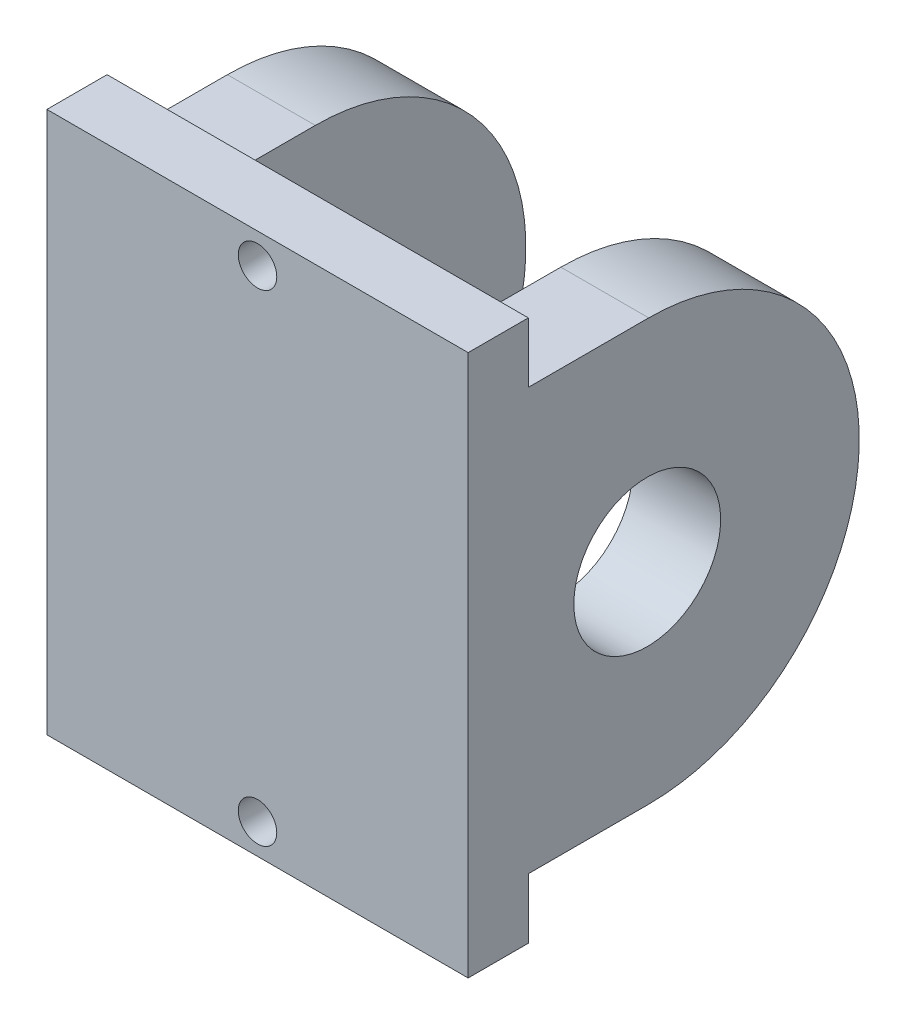
SolidWorks part; units mm, degrees
ref_plane "前视基准面" through (0, 0, 0) normal (0, 0, 1) x (1, 0, 0)
ref_plane "上视基准面" through (0, 0, 0) normal (0, 1, 0) x (1, 0, 0)
ref_plane "右视基准面" through (0, 0, 0) normal (1, 0, 0) x (0, 0, -1)
other "Configuration Table"
sketch "草图1" plane through (0, 0, 0) normal (0, 0, 1) x (1, 0, 0)
  line L1 (-17.5, 17.5) -> (17.5, 17.5)
  line L2 (-17.5, 17.5) -> (-17.5, -17.5)
  line L3 (-17.5, -17.5) -> (17.5, -17.5)
  line L4 (17.5, 17.5) -> (17.5, -17.5)
  line L5 (0, -17.5) -> (0, 17.5) construction
  line L6 (-17.5, 0) -> (17.5, 0) construction
  point P0 (0, 0)
  dimension "D1" = 35
  dimension "D2" = 35
extrude "凸台-拉伸1" add sketch "草图1" along normal blind 5
sketch "草图2" plane through (-17.5, 0, 0) normal (-1, 0, 0) x (0, 0, 1)
  line L1 (5, 17.5) -> (-10, 17.5)
  line L2 (5, 17.5) -> (5, -17.5)
  line L3 (5, -17.5) -> (-10, -17.5)
  line L5 (5, -17.5) -> (0, -17.5) construction
  line L6 (0, 17.5) -> (0, -17.5) construction
  line L7 (-10, 17.5) -> (-10, 17.497)
  line L8 (-10, -17.497) -> (-10, -17.5)
  arc A0 (-10, 17.497) -> (-10, -17.497) centre (-10, 0) ccw
  point P11 (0, 0)
  dimension "D1" = 15
  dimension "D2" = 15
  dimension "D3" = 10
extrude "凸台-拉伸2" add sketch "草图2" against normal blind 7.3
sketch "草图3" plane through (17.5, 0, 0) normal (1, 0, 0) x (0, 0, -1)
  line L5 (10, 17.5) -> (-5, 17.5)
  line L6 (10, 17.497) -> (10, 17.5)
  line L7 (10, -17.5) -> (10, -17.497)
  line L8 (-5, -17.5) -> (10, -17.5)
  line L9 (-5, 17.5) -> (-5, -17.5)
  line L10 (10, 17.5) -> (-5, 17.5)
  line L11 (10, 17.497) -> (10, 17.5)
  line L12 (10, -17.5) -> (10, -17.497)
  line L13 (-5, -17.5) -> (10, -17.5)
  line L14 (-5, 17.5) -> (-5, -17.5)
  arc A1 (10, -17.497) -> (10, 17.497) centre (10, 0) ccw
  arc A2 (10, -17.497) -> (10, 17.497) centre (10, 0) ccw
  dimension "D1" = 0
extrude "凸台-拉伸3" add sketch "草图3" against normal blind 7.3
sketch "草图4" plane through (0, 0, 5) normal (0, 0, 1) x (1, 0, 0)
  line L1 (-17.5, 22.5) -> (17.5, 22.5)
  line L2 (-17.5, 22.5) -> (-17.5, -22.5)
  line L3 (-17.5, -22.5) -> (17.5, -22.5)
  line L4 (17.5, 22.5) -> (17.5, -22.5)
  line L5 (0, -22.5) -> (0, 22.5) construction
  line L6 (-17.5, 0) -> (17.5, 0) construction
  point P0 (0, 0)
  dimension "D1" = 35
  dimension "D2" = 45
extrude "凸台-拉伸4" add sketch "草图4" against normal blind 5
sketch "草图6" plane through (-10.2, 0, 0) normal (1, 0, 0) x (0, 0, -1)
  circle A0 centre (9.8805, 0) radius 6.1
  point P0 (9.8805, 0)
  dimension "D1" = 12.2
extrude "切除-拉伸1" cut sketch "草图6" against normal through all
sketch "草图7" plane through (10.2, 0, 0) normal (-1, 0, 0) x (0, 0, 1)
  circle A1 centre (-9.8805, 0) radius 6.1
  circle A2 centre (-9.8805, 0) radius 6.1
  dimension "D1" = 0
extrude "切除-拉伸2" cut sketch "草图7" against normal through all
sketch "草图8" plane through (0, 0, 0) normal (0, 0, -1) x (-1, 0, 0)
  line L0 (17.5, 22.5) -> (17.5, 17.5) construction
  circle A0 centre (0, 20) radius 1.6
  circle A1 centre (0, -20) radius 1.6
  point P4 (0, 0)
  dimension "D1" = 3.2
  dimension "D2" = 3.2
  dimension "D3" = 20
  dimension "D4" = 20
  dimension "D5" = 17.5
extrude "切除-拉伸3" cut sketch "草图8" against normal blind 10
